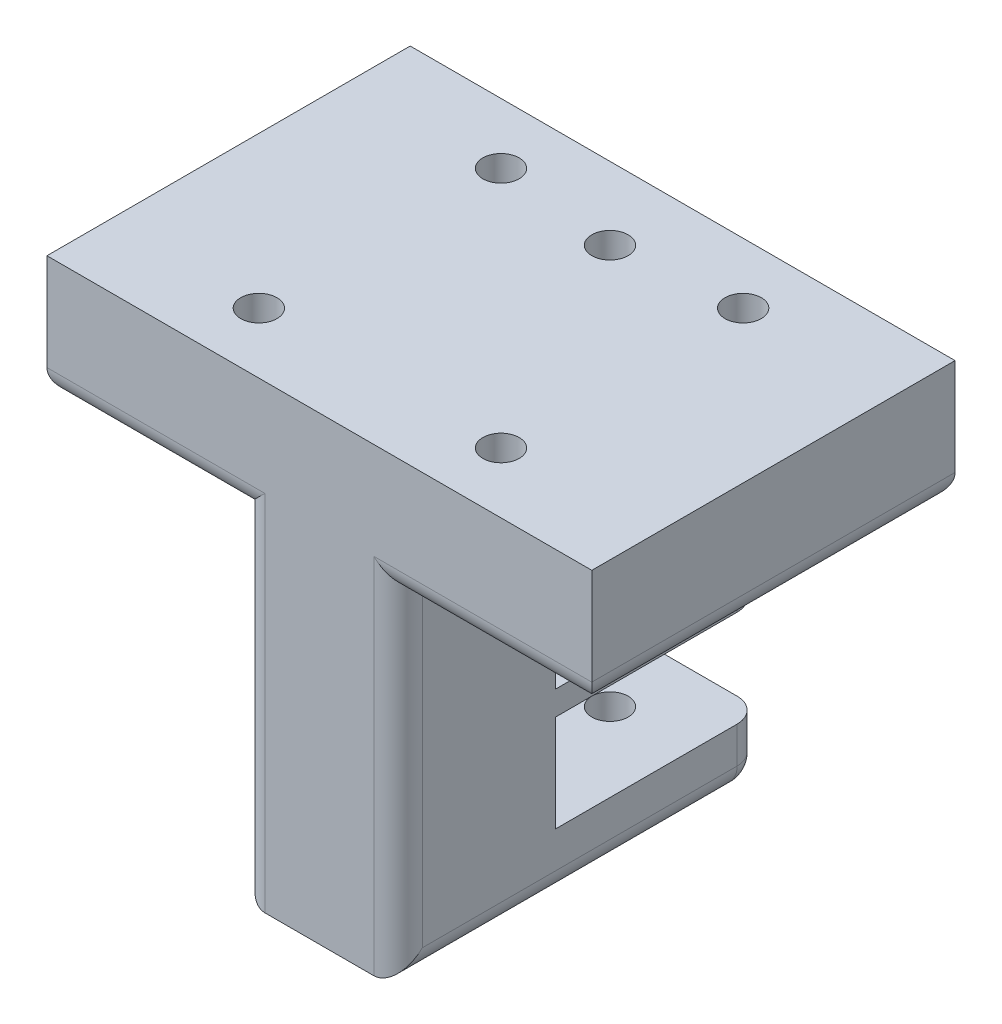
SolidWorks part; units mm, degrees
ref_plane "Front Plane" through (0, 0, 0) normal (0, 0, 1) x (1, 0, 0)
ref_plane "Top Plane" through (0, 0, 0) normal (0, 1, 0) x (1, 0, 0)
ref_plane "Right Plane" through (0, 0, 0) normal (1, 0, 0) x (0, 0, -1)
sketch "Sketch1" plane through (0, 0, 0) normal (0, 1, 0) x (1, 0, 0)
  line L1 (-20.4957, 14.8137) -> (24.5043, 14.8137)
  line L2 (-20.4957, 14.8137) -> (-20.4957, -15.1863)
  line L3 (-20.4957, -15.1863) -> (24.5043, -15.1863)
  line L4 (24.5043, 14.8137) -> (24.5043, -15.1863)
  line L5 (-20.4957, 14.8137) -> (24.5043, -15.1863) construction
  line L6 (-20.4957, -15.1863) -> (24.5043, 14.8137) construction
  line L11 (-7.9957, 9.8137) -> (12.0043, 9.8137) construction
  line L12 (-7.9957, 9.8137) -> (-7.9957, -10.1863) construction
  line L13 (-7.9957, -10.1863) -> (12.0043, -10.1863) construction
  line L14 (12.0043, 9.8137) -> (12.0043, -10.1863) construction
  line L15 (-7.9957, 9.8137) -> (12.0043, -10.1863) construction
  line L16 (-7.9957, -10.1863) -> (12.0043, 9.8137) construction
  circle A0 centre (-7.9957, 9.8137) radius 1.5
  circle A1 centre (12.0043, 9.8137) radius 1.5
  circle A2 centre (12.0043, -10.1863) radius 1.5
  circle A3 centre (-7.9957, -10.1863) radius 1.5
  point P0 (2.0043, -0.1863)
  dimension "D1" = 3
  dimension "D2" = 45
  dimension "D3" = 30
  dimension "D4" = 20
  dimension "D5" = 20
extrude "Boss-Extrude1" add sketch "Sketch1" against normal blind 10
sketch "Sketch5" plane through (0, -10, 0) normal (0, -1, 0) x (1, 0, 0)
  line L0 (-20.4957, 15.1863) -> (24.5043, 15.1863) construction
  line L1 (-4.4957, 15.1863) -> (8.5043, 15.1863)
  line L2 (-4.4957, 15.1863) -> (-4.4957, -14.8137)
  line L3 (-4.4957, -14.8137) -> (8.5043, -14.8137)
  line L4 (8.5043, 15.1863) -> (8.5043, -14.8137)
  line L5 (-20.4957, -14.8137) -> (24.5043, -14.8137) construction
  line L6 (-20.4957, -14.8137) -> (-20.4957, 15.1863) construction
  line L7 (-20.4957, 15.1863) -> (24.5043, 15.1863) construction
  line L8 (-20.4957, 15.1863) -> (-20.4957, -14.8137) construction
  line L9 (-20.4957, -14.8137) -> (24.5043, -14.8137) construction
  line L10 (24.5043, 15.1863) -> (24.5043, -14.8137) construction
  line L11 (-20.4957, 15.1863) -> (24.5043, -14.8137) construction
  line L12 (-20.4957, -14.8137) -> (24.5043, 15.1863) construction
  line L13 (2.0043, -999.8137) -> (2.0043, 49000.1863) construction
  point P8 (2.0043, 0.1863)
  dimension "D1" = 13
extrude "Boss-Extrude2" add sketch "Sketch5" along normal blind 28
sketch "Sketch6" plane through (0, -38, 0) normal (0, -1, 0) x (1, 0, 0)
  line L0 (8.5043, -14.8137) -> (8.5043, 15.1863) construction
  line L1 (-4.4957, 15.1863) -> (8.5043, 15.1863)
  line L2 (-4.4957, 15.1863) -> (-4.4957, 5.1863)
  line L3 (-4.4957, 5.1863) -> (8.5043, 5.1863)
  line L4 (8.5043, 15.1863) -> (8.5043, 5.1863)
  line L5 (2.0043, 5.1863) -> (2.0043, 15.1863) construction
  line L6 (-4.4957, 10.1863) -> (8.5043, 10.1863) construction
  point P232 (2.0043, 10.1863)
  dimension "D1" = 10
sketch "Sketch7" plane through (0, 0, -14.8137) normal (0, 0, -1) x (-1, 0, 0)
  line L0 (-8.5043, -38) -> (-8.5043, -10) construction
  line L1 (-8.5043, -33) -> (4.4957, -33)
  line L2 (-8.5043, -33) -> (-8.5043, -25)
  line L3 (-8.5043, -25) -> (4.4957, -25)
  line L4 (4.4957, -33) -> (4.4957, -25)
  line L5 (-2.0043, -25) -> (-2.0043, -33) construction
  line L6 (-8.5043, -29) -> (4.4957, -29) construction
  line L7 (4.4957, -38) -> (4.4957, -10) construction
  line L8 (20.4957, -10) -> (4.4957, -10) construction
  line L9 (-8.5043, -15) -> (4.4957, -15)
  line L10 (-8.5043, -15) -> (-8.5043, -23)
  line L11 (-8.5043, -23) -> (4.4957, -23)
  line L12 (4.4957, -15) -> (4.4957, -23)
  line L13 (-2.0043, -23) -> (-2.0043, -15) construction
  line L14 (-8.5043, -19) -> (4.4957, -19) construction
  line L15 (4.4957, -38) -> (-8.5043, -38) construction
  point P108 (-2.0043, -19)
  point P256 (-2.0043, -29)
  dimension "D1" = 5
  dimension "D2" = 5
  dimension "D3" = 8
extrude "Cut-Extrude1" cut sketch "Sketch7" against normal blind 17
sketch "Sketch8" plane through (0, -38, 0) normal (0, -1, 0) x (1, 0, 0)
  line L0 (-4.4957, 15.1863) -> (8.5043, -14.8137) construction
  line L1 (8.5043, 15.1863) -> (-4.4957, -14.8137) construction
  line L2 (2.0043, -995.0009) -> (2.0043, 49004.9991) construction
  line L3 (8.5043, 15.1863) -> (-4.4957, 15.1863) construction
  circle A0 centre (2.0043, -8.8137) radius 1.5
  point P13 (2.0043, 0.1863)
  dimension "D1" = 3
  dimension "D2" = 24
extrude "Cut-Extrude2" cut sketch "Sketch8" against normal through all
fillet "Fillet1" radius 2 17 edges at (8.5043, -38, 0.1863) (-4.4957, -38, 0.1863) (-12.4957, -10, 15.1863) (16.5043, -10, 15.1863) (-20.4957, -10, 0.1863) (24.5043, -10, 0.1863) (-12.4957, -10, -14.8137) (16.5043, -10, -14.8137) (8.5043, -12.5, -14.8137) (8.5043, -24, -14.8137) (8.5043, -35.5, -14.8137) (-4.4957, -12.5, -14.8137) (-4.4957, -24, -14.8137) (-4.4957, -35.5, -14.8137) (8.5043, -24, 15.1863) (-4.4957, -24, 15.1863) (2.0043, -38, -14.8137)
